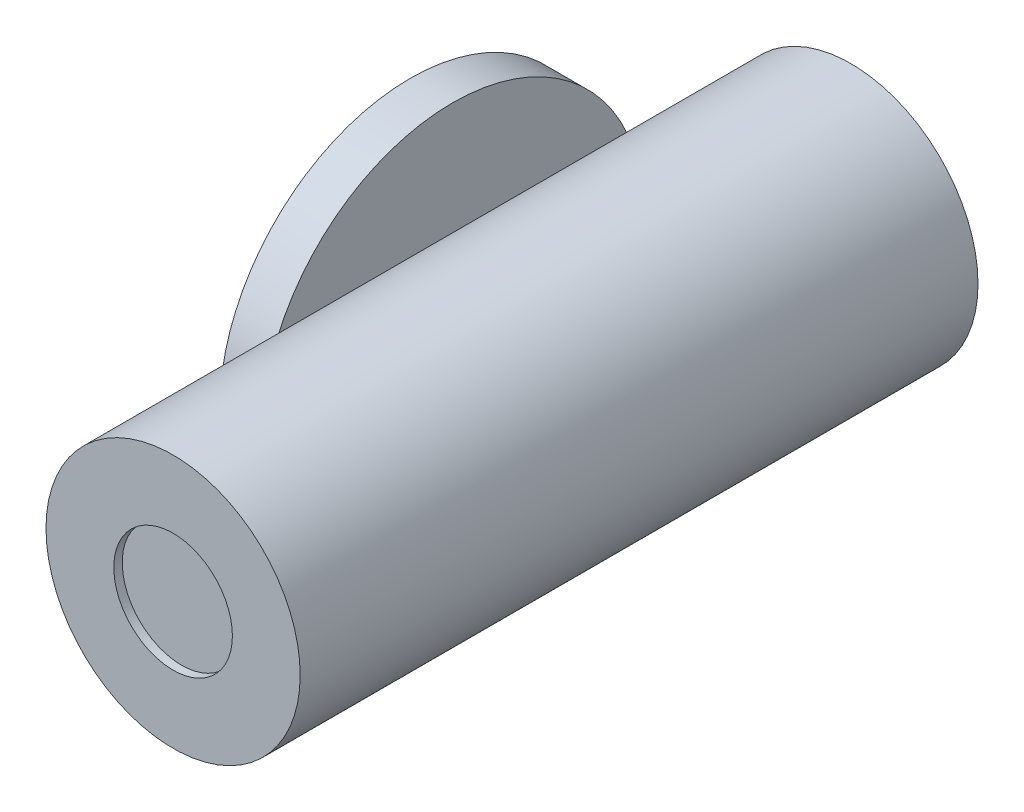
SolidWorks part; units mm, degrees
ref_plane "Plan de face" through (0, 0, 0) normal (0, 0, 1) x (1, 0, 0)
ref_plane "Plan de dessus" through (0, 0, 0) normal (0, 1, 0) x (1, 0, 0)
ref_plane "Plan de droite" through (0, 0, 0) normal (1, 0, 0) x (0, 0, -1)
sketch "Esquisse1" plane through (0, 0, 0) normal (0, 0, 1) x (1, 0, 0)
  circle A0 centre (0, 0) radius 150
  dimension "D1" = 300
extrude "Boss.-Extru.1" add sketch "Esquisse1" against normal blind 800
sketch3d "Esquisse3D1" plane through (0, 0, 0) normal (0, 0, 1) x (1, 0, 0)
  dimension "D1" = 120
sketch "Esquisse2" plane through (-120, 0, 0) normal (1, 0, 0) x (0, 0, -1)
  line L0 (800, -150) -> (800, 150) construction
  line L1 (800, 150) -> (0, 150) construction
  circle A0 centre (450, 0) radius 225
  dimension "D1" = 450
  dimension "D2" = 350
  dimension "D3" = 150
extrude "Boss.-Extru.2" add sketch "Esquisse2" against normal blind 50
sketch "Esquisse3" plane through (-170, 0, 0) normal (-1, 0, 0) x (0, 0, 1)
  circle A0 centre (-450, 0) radius 70
  dimension "D1" = 140
sketch "Esquisse4" plane through (0, 0, 0) normal (0, 0, 1) x (1, 0, 0)
  circle A0 centre (0, 0) radius 70
  dimension "D1" = 140
extrude "Enlèv. mat.-Extru.2" cut sketch "Esquisse4" against normal blind 10
extrude "Boss.-Extru.3" add sketch "Esquisse3" along normal blind 10
